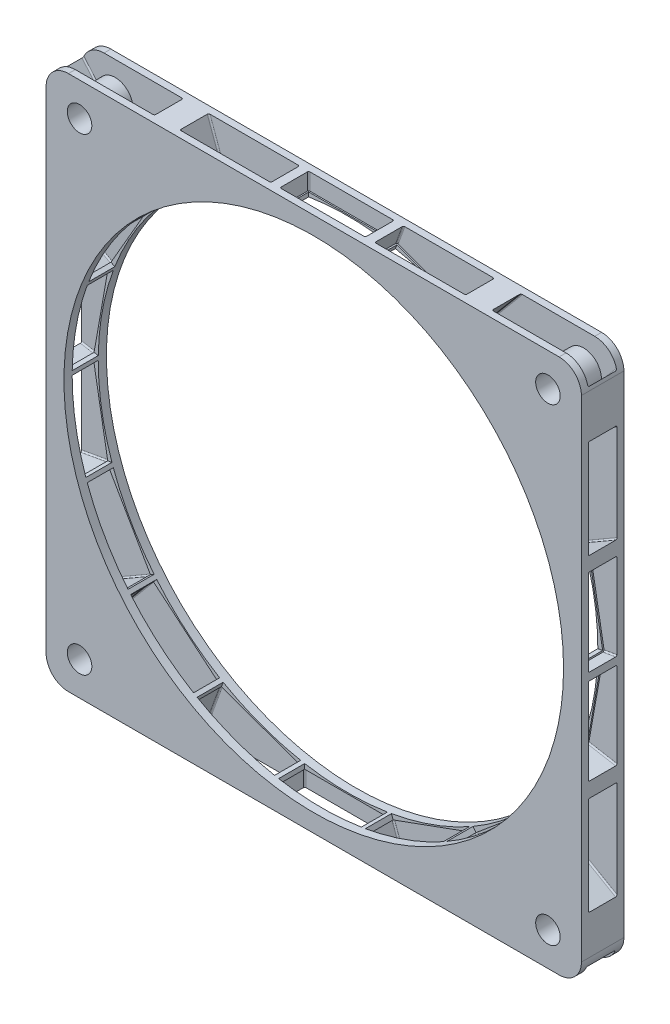
SolidWorks part; units mm, degrees
ref_plane "Front Plane" through (0, 0, 0) normal (0, 0, 1) x (1, 0, 0)
ref_plane "Top Plane" through (0, 0, 0) normal (0, 1, 0) x (1, 0, 0)
ref_plane "Right Plane" through (0, 0, 0) normal (1, 0, 0) x (0, 0, -1)
sketch "Sketch1" plane through (0, 0, 0) normal (0, 0, 1) x (1, 0, 0)
  line L1 (-55, -60) -> (55, -60)
  line L2 (-60, -55) -> (-60, 55)
  line L3 (-55, 60) -> (55, 60)
  line L4 (60, -55) -> (60, 55)
  line L5 (-60, -60) -> (60, 60) construction
  line L6 (-60, 60) -> (60, -60) construction
  circle A0 centre (0, 0) radius 56
  circle A1 centre (-52.5, 52.5) radius 2.75
  circle A2 centre (52.5, 52.5) radius 2.75
  circle A3 centre (52.5, -52.5) radius 2.75
  circle A4 centre (-52.5, -52.5) radius 2.75
  arc A5 (-55, -60) -> (-60, -55) centre (-55, -55) cw
  arc A6 (55, -60) -> (60, -55) centre (55, -55) ccw
  arc A7 (55, 60) -> (60, 55) centre (55, 55) cw
  arc A8 (-60, 55) -> (-55, 60) centre (-55, 55) cw
  point P18 (0, 0)
  dimension "D1" = 112
  dimension "D3" = 5.5
  dimension "D6" = 5
  dimension "D2" = 120
  dimension "D5" = 105
  dimension "D4" = 4
extrude "Boss-Extrude1" add sketch "Sketch1" along normal mid plane 9.525
sketch "Sketch6" plane through (-0.4461, -56.254, 0) normal (0, -1, 0) x (1, 0, 0)
  line L4 (9.271, 2.921) -> (-9.271, 2.921)
  line L5 (9.271, -2.921) -> (9.271, 2.921)
  line L6 (-9.271, -2.921) -> (9.271, -2.921)
  line L7 (-9.271, 2.921) -> (-9.271, -2.921)
  line L8 (9.271, 2.921) -> (-9.271, 2.921)
  line L9 (9.271, -2.921) -> (9.271, 2.921)
  line L10 (-9.271, -2.921) -> (9.271, -2.921)
  line L11 (-9.271, 2.921) -> (-9.271, -2.921)
  dimension "D1" = 0
extrude "Cut-Extrude5" cut sketch "Sketch6" against normal up to next and the other way through all
sketch "Sketch7" plane through (-0.4461, -56.254, 0) normal (0, -1, 0) x (1, 0, 0)
  line L0 (9.525, -2.921) -> (9.525, 2.921) construction
  line L1 (9.271, 3.175) -> (-9.271, 3.175) construction
  line L2 (-9.271, -3.175) -> (9.271, -3.175) construction
  line L3 (-9.525, 2.921) -> (-9.525, -2.921) construction
  line L4 (-9.271, -3.175) -> (9.271, -3.175) construction
  line L5 (-9.525, 2.921) -> (-9.525, -2.921) construction
  line L6 (9.271, 3.175) -> (-9.271, 3.175) construction
  line L7 (9.525, -2.921) -> (9.525, 2.921) construction
  line L8 (9.575, -2.921) -> (9.575, 2.921)
  line L9 (9.271, 3.225) -> (-9.271, 3.225)
  line L10 (-9.575, 2.921) -> (-9.575, -2.921)
  line L11 (-9.271, -3.225) -> (9.271, -3.225)
  arc A0 (-9.271, 3.175) -> (-9.525, 2.921) centre (-9.271, 2.921) ccw construction
  arc A1 (9.525, 2.921) -> (9.271, 3.175) centre (9.271, 2.921) ccw construction
  arc A2 (9.271, -3.175) -> (9.525, -2.921) centre (9.271, -2.921) ccw construction
  arc A3 (-9.525, -2.921) -> (-9.271, -3.175) centre (-9.271, -2.921) ccw construction
  arc A4 (9.271, -3.175) -> (9.525, -2.921) centre (9.271, -2.921) ccw construction
  arc A5 (-9.525, -2.921) -> (-9.271, -3.175) centre (-9.271, -2.921) ccw construction
  arc A6 (-9.271, 3.175) -> (-9.525, 2.921) centre (-9.271, 2.921) ccw construction
  arc A7 (9.525, 2.921) -> (9.271, 3.175) centre (9.271, 2.921) ccw construction
  arc A8 (9.271, -3.225) -> (9.575, -2.921) centre (9.271, -2.921) ccw
  arc A9 (9.575, 2.921) -> (9.271, 3.225) centre (9.271, 2.921) ccw
  arc A10 (-9.271, 3.225) -> (-9.575, 2.921) centre (-9.271, 2.921) ccw
  arc A11 (-9.575, -2.921) -> (-9.271, -3.225) centre (-9.271, -2.921) ccw
  dimension "D1" = 0.05
extrude "Cut-Extrude6" cut sketch "Sketch7" along normal through all
pattern_circular "CirPattern9" count 18 over 360 about axis through (0, 0, 0) along (0, 0, 1) of "Cut-Extrude5", "Cut-Extrude6"
sketch "Sketch8" plane through (0, 0, 3.225) normal (0, 0, -1) x (-1, 0, 0)
  circle A0 centre (-52.5, 52.5) radius 2.75 construction
  circle A1 centre (-52.5, 52.5) radius 2.75
  circle A2 centre (-52.5, 52.5) radius 4
  dimension "D1" = 1.25
extrude "Boss-Extrude2" add sketch "Sketch8" along normal up to next
pattern_circular "CirPattern10" count 4 over 360 about axis through (0, 0, 0) along (0, 0, 1) of "Boss-Extrude2"
